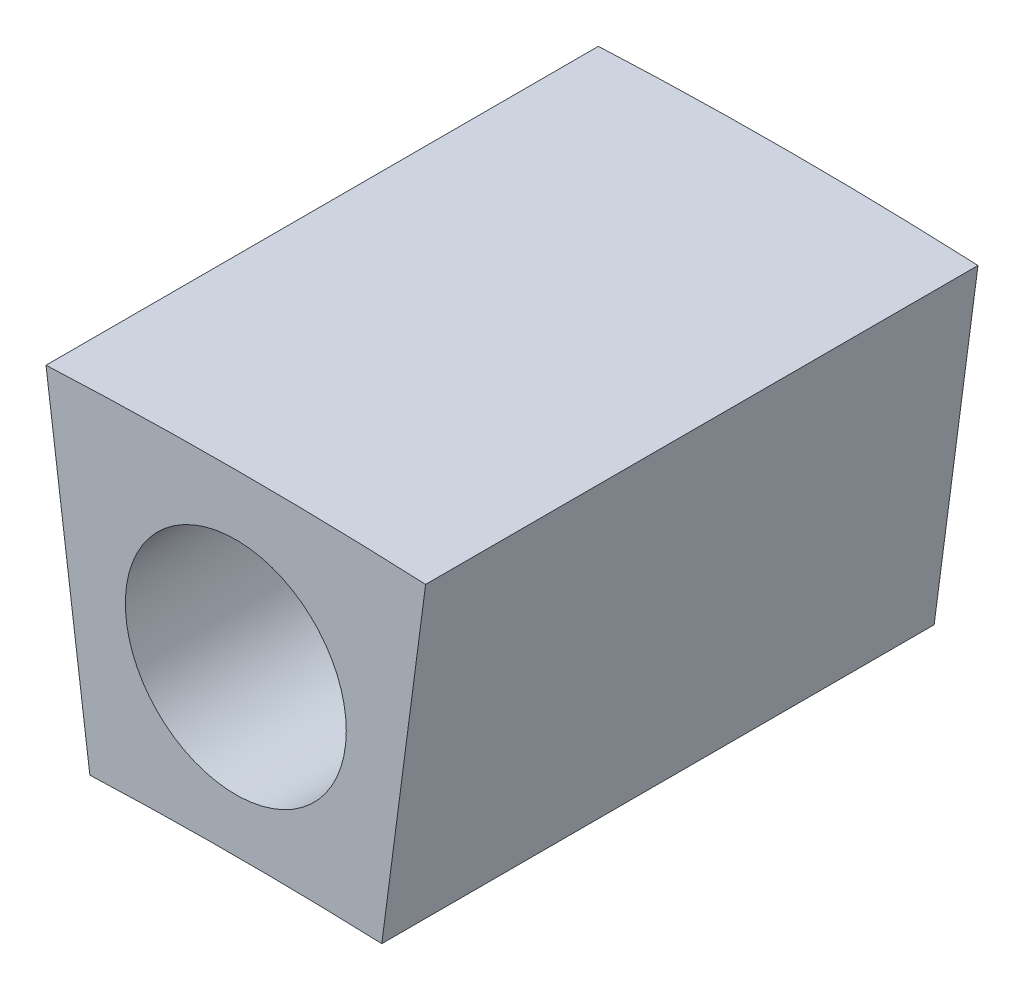
SolidWorks part; units mm, degrees
ref_plane "Front Plane" through (0, 0, 0) normal (0, 0, 1) x (1, 0, 0)
ref_plane "Top Plane" through (0, 0, 0) normal (0, 1, 0) x (1, 0, 0)
ref_plane "Right Plane" through (0, 0, 0) normal (1, 0, 0) x (0, 0, -1)
sketch "Sketch1" plane through (0, 0, 0) normal (0, 0, 1) x (-1, 0, 0)
  line L6 (5.1544, -5.123) -> (3.9636, 3.9223)
  line L7 (-3.9636, 3.9223) -> (-5.1544, -5.123)
  arc A6 (-3.9636, 3.9223) -> (3.9636, 3.9223) centre (0, 107.5507) ccw
  arc A7 (-5.1544, -5.123) -> (5.1544, -5.123) centre (0, 107.3051) ccw
extrude "Boss-Extrude1" add sketch "Sketch1" along normal mid plane 15 contours A7 L6 A6 L7
sketch "Sketch2" plane through (0, 0, 7.5) normal (0, 0, 1) x (1, 0, 0)
  line L0 (-4.559, 0.6004) -> (4.559, 0.6004) construction
  line L1 (-5.1544, 5.123) -> (-3.9636, -3.9223) construction
  line L2 (3.9636, -3.9223) -> (5.1544, 5.123) construction
  line L3 (0, -3.8465) -> (0, 5.2411) construction
  arc A0 (3.9636, -3.9223) -> (-3.9636, -3.9223) centre (0, -107.5507) ccw construction
  arc A1 (5.1544, 5.123) -> (-5.1544, 5.123) centre (0, -107.3051) ccw construction
  circle A2 centre (0, 0.6004) radius 3
  dimension "D1" = 6
extrude "Cut-Extrude1" cut sketch "Sketch2" against normal blind 15
